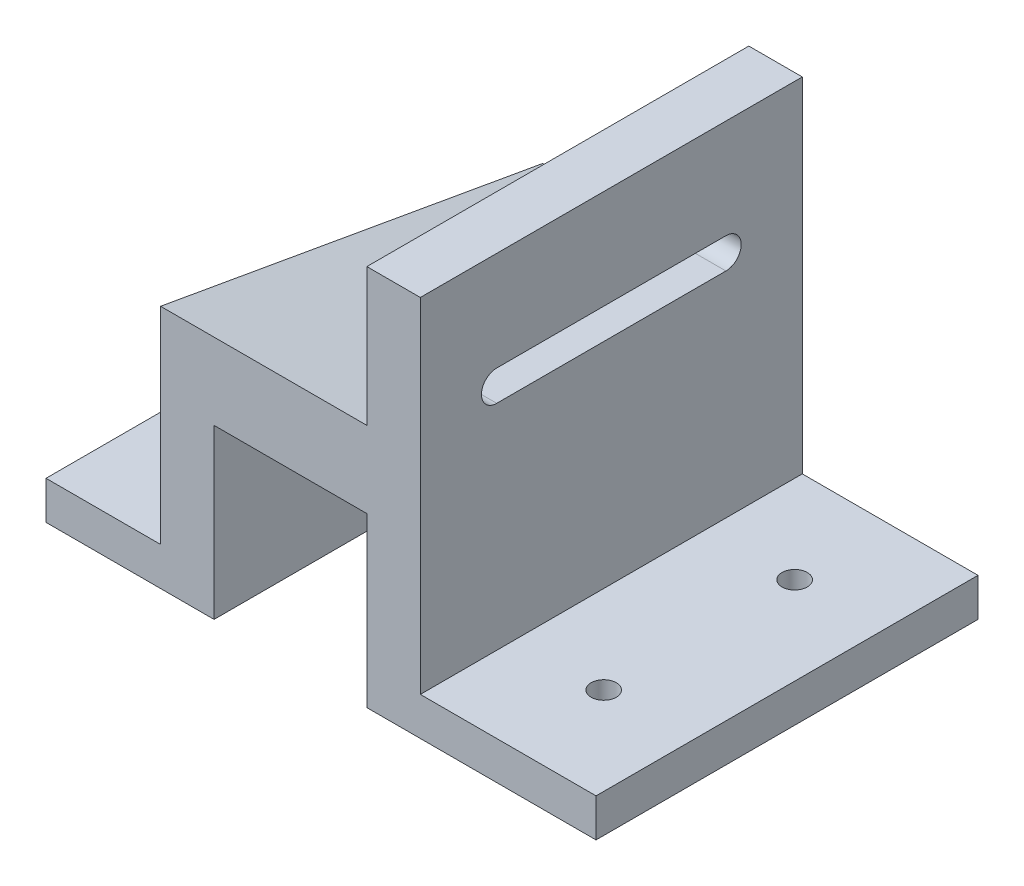
SolidWorks part; units mm, degrees
ref_plane "Plano frontal" through (0, 0, 0) normal (0, 0, 1) x (1, 0, 0)
ref_plane "Plano superior" through (0, 0, 0) normal (0, 1, 0) x (1, 0, 0)
ref_plane "Plano direito" through (0, 0, 0) normal (1, 0, 0) x (0, 0, -1)
sketch "Esboço2" plane through (0, 0, 0) normal (0, 0, 1) x (1, 0, 0)
  line L0 (0, 0) -> (30, 0)
  line L1 (30, 0) -> (30, 5)
  line L2 (30, 5) -> (7, 5)
  line L3 (7, 5) -> (7, 50)
  line L4 (7, 50) -> (0, 50)
  line L5 (0, 50) -> (0, 32)
  line L6 (-20, 0) -> (-42, 0)
  line L7 (-42, 0) -> (-42, 5)
  line L8 (-42, 5) -> (-27, 5)
  line L9 (-27, 5) -> (-27, 32)
  line L10 (-27, 32) -> (-20, 32)
  line L11 (-20, 0) -> (-20, 7)
  line L12 (-20, 32) -> (0, 32)
  line L13 (-20, 7) -> (0, 7)
  line L14 (0, 7) -> (0, 0)
  dimension "D1" = 5
  dimension "D2" = 30
  dimension "D3" = 7
  dimension "D4" = 50
  dimension "D5" = 25
  dimension "D6" = 15
  dimension "D7" = 32
extrude "Ressalto-extrusão1" add sketch "Esboço2" along normal blind 50
sketch "Esboço3" plane through (7, 0, 0) normal (1, 0, 0) x (0, 0, -1)
  line L0 (-25, 50) -> (-25, 5) construction
  line L1 (-50, 50) -> (0, 50) construction
  line L2 (-50, 5) -> (0, 5) construction
  line L3 (-40, 35) -> (-10, 35) construction
  line L4 (-40, 37) -> (-10, 37)
  line L5 (-40, 33) -> (-10, 33)
  line L6 (-40, 15) -> (-10, 15) construction
  line L7 (-40, 17) -> (-10, 17)
  line L8 (-40, 13) -> (-10, 13)
  arc A0 (-40, 37) -> (-40, 33) centre (-40, 35) ccw
  arc A1 (-10, 33) -> (-10, 37) centre (-10, 35) ccw
  arc A2 (-40, 17) -> (-40, 13) centre (-40, 15) ccw
  arc A3 (-10, 13) -> (-10, 17) centre (-10, 15) ccw
  point P8 (-25, 35)
  point P14 (-25, 15)
  dimension "D1" = 2
  dimension "D2" = 30
  dimension "D3" = 20
  dimension "D4" = 10
extrude "Corte-extrusão1" cut sketch "Esboço3" against normal blind 50 contours L5 A1 L4 A0
sketch "Esboço4" plane through (0, 0, 0) normal (-1, 0, 0) x (0, 0, 1)
  line L0 (50, 32) -> (94.0881, 39.7739) construction
  line L6 (50, 50) -> (50, 32) construction
  point P4 (26.6519, 4.9065)
  point P5 (17.3646, 13)
  point P6 (18, 23.8935)
  point P7 (50, 25)
  point P11 (22, 24)
  dimension "D1" = 80
sketch "Esboço5" plane through (0, 5, 0) normal (0, 1, 0) x (1, 0, 0)
  line L0 (7, -25) -> (30, -25) construction
  line L1 (7, -50) -> (7, 0) construction
  line L2 (30, -50) -> (30, 0) construction
  line L3 (30, -50) -> (7, -50) construction
  line L4 (-8, 1.6575) -> (-8, -52.8314) construction
  line L5 (-23, -25) -> (-46, -25) construction
  line L6 (-27, 0) -> (-42, 0) construction
  circle A0 centre (18.5, -37.5) radius 1.65
  circle A1 centre (18.5, -12.5) radius 1.65
  circle A2 centre (-34.5, -12.5) radius 1.65
  circle A3 centre (-34.5, -37.5) radius 1.65
  point P13 (18.5, -50)
  point P21 (0, 0)
  point P24 (-34.5, 0)
  dimension "D1" = 3.3
  dimension "D2" = 25
extrude "Corte-extrusão2" cut sketch "Esboço5" against normal blind 10
sketch "Esboço7" plane through (0, 0, 50) normal (0, 0, 1) x (1, 0, 0)
  line L0 (0, 32) -> (-27, 32)
  line L1 (-27, 32) -> (-27, 41.3868)
  line L2 (-27, 41.3868) -> (0, 41.3868)
  line L3 (0, 50) -> (0, 32) construction
  line L4 (0, 41.3868) -> (0, 32)
  line L5 (-20, 7) -> (-20, 22)
  line L6 (-20, 22) -> (0, 22)
  line L7 (0, 22) -> (0, 7)
  line L8 (0, 7) -> (-20, 7)
  dimension "D1" = 10
extrude "Corte-extrusão3" cut sketch "Esboço7" along direction (0, 0.1736, 0.9848) on the side against the normal through all
sketch "Esboço8" plane through (0, 12.7861, -2.2545) normal (0, -0.9848, 0.1736) x (1, 0, 0)
  line L0 (0, 2.2893) -> (0, 53.0606) construction
  line L1 (0, 53.0606) -> (-20, 53.0606) construction
  circle A0 centre (-10, 27.675) radius 4.15
  point P2 (0, 0)
  point P5 (0, 27.675)
  point P6 (0, 0)
  point P9 (-10, 53.0606)
  dimension "D1" = 8.3
extrude "Corte-extrusão4" cut sketch "Esboço8" against normal through all
